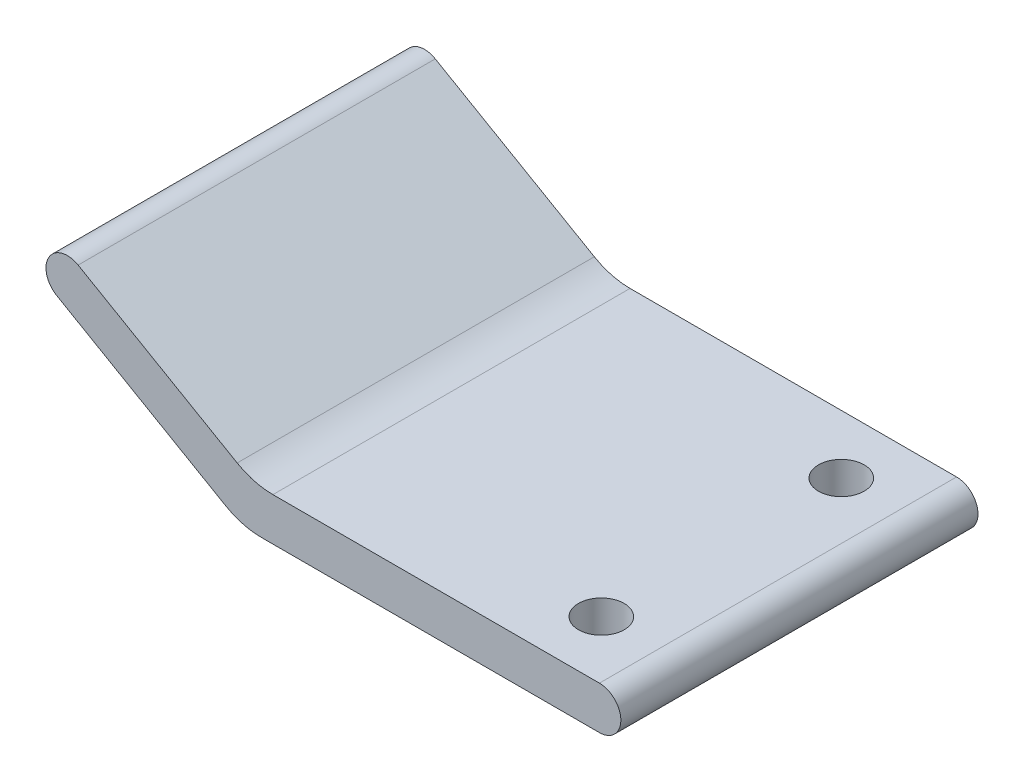
SolidWorks part; units mm, degrees
ref_plane "Front Plane" through (0, 0, 0) normal (0, 0, 1) x (1, 0, 0)
ref_plane "Top Plane" through (0, 0, 0) normal (0, 1, 0) x (1, 0, 0)
ref_plane "Right Plane" through (0, 0, 0) normal (1, 0, 0) x (0, 0, -1)
sketch "Sketch1" plane through (0, 0, 0) normal (0, 0, 1) x (1, 0, 0)
  line L0 (0, 0) -> (-25, 0)
  line L1 (-25, 0) -> (-37.9904, 7.5)
  line L2 (0, 3) -> (-24.1962, 3)
  line L3 (-24.1962, 3) -> (-36.4904, 10.0981)
  arc A0 (0, 0) -> (0, 3) centre (0, 1.5) ccw
  arc A1 (-37.9904, 7.5) -> (-36.4904, 10.0981) centre (-37.2404, 8.799) cw
  dimension "D1" = 30
  dimension "D2" = 25
  dimension "D3" = 15
  dimension "D4" = 3
extrude "Boss-Extrude1" add sketch "Sketch1" along normal mid plane 25
sketch "Sketch2" plane through (0, 3, 0) normal (0, 1, 0) x (1, 0, 0)
  line L0 (-24.1962, 0) -> (0, 0) construction
  line L1 (-24.1962, 12.5) -> (0, -12.5) construction
  line L4 (0, 12.5) -> (-24.1962, 12.5)
  line L5 (-24.1962, 12.5) -> (-24.1962, -12.5)
  line L6 (-24.1962, -12.5) -> (0, -12.5)
  line L7 (0, -12.5) -> (0, 12.5)
  line L8 (0, 12.5) -> (-24.1962, 12.5)
  line L9 (-24.1962, 12.5) -> (-24.1962, -12.5)
  line L10 (-24.1962, -12.5) -> (0, -12.5)
  line L11 (0, -12.5) -> (0, 12.5)
  circle A0 centre (-3.9682, -8.4) radius 1.6
  point P2 (-24.1962, 0)
  dimension "D2" = 3.2
  dimension "D3" = 8.4
  dimension "D1" = 0
extrude "Cut-Extrude1" cut sketch "Sketch2" against normal through all both and the other way through all contours A0
mirror "Mirror1" about plane through (0, 0, 0) normal (0, 0, 1) of "Cut-Extrude1"
fillet "Fillet1" radius 5 2 edges at (-24.1962, 3, 0) (-25, 0, 0)
